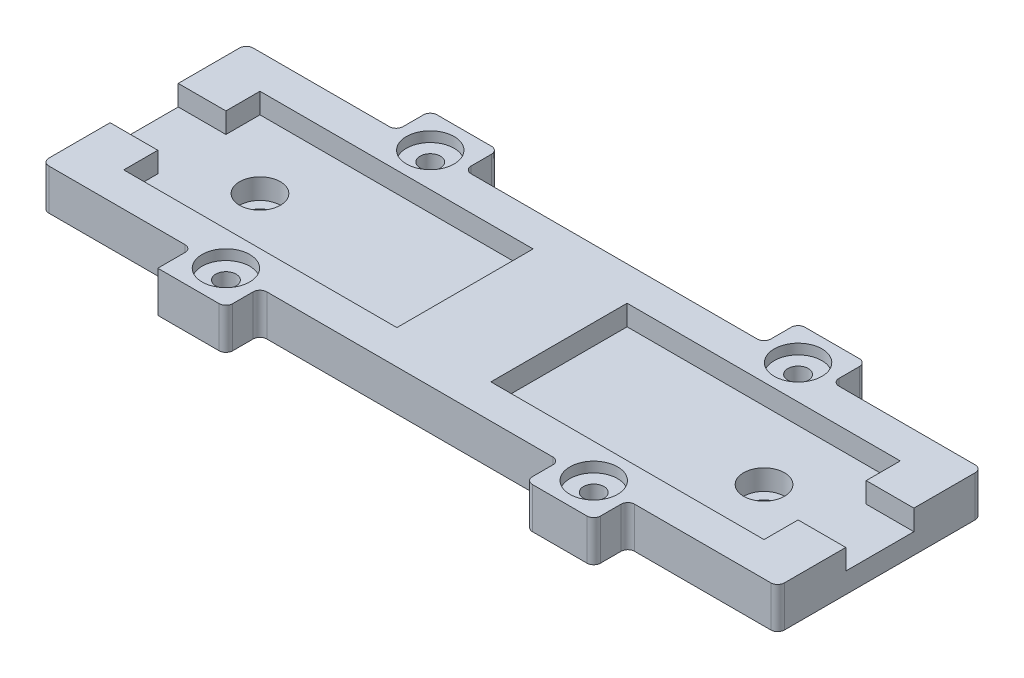
SolidWorks part; units mm, degrees
material "ABS"
ref_plane "前视基准面" through (0, 0, 0) normal (0, 0, 1) x (1, 0, 0)
ref_plane "上视基准面" through (0, 0, 0) normal (0, 1, 0) x (1, 0, 0)
ref_plane "右视基准面" through (0, 0, 0) normal (1, 0, 0) x (0, 0, -1)
sketch "草图1" plane through (0, 0, 0) normal (0, 1, 0) x (1, 0, 0)
  line L0 (-65.1948, 0) -> (81.9903, 0) construction
  line L1 (-54, -15) -> (54, -15)
  line L2 (-54, -15) -> (-54, 15)
  line L3 (-54, 15) -> (54, 15)
  line L4 (54, -15) -> (54, 15)
  line L5 (-54, -15) -> (54, 15) construction
  line L6 (-54, 15) -> (54, -15) construction
  line L7 (0, 35.3859) -> (0, -29.3601) construction
  line L8 (-27, 35.3859) -> (-27, -29.3601) construction
  line L9 (-32, 15) -> (-32, 20)
  line L10 (-32, 20) -> (-22, 20)
  line L11 (-22, 20) -> (-22, 15)
  line L12 (22, 20) -> (22, 15)
  line L13 (32, 20) -> (22, 20)
  line L14 (32, 15) -> (32, 20)
  line L15 (32, -15) -> (32, -20)
  line L16 (32, -20) -> (22, -20)
  line L17 (22, -20) -> (22, -15)
  line L18 (-22, -20) -> (-22, -15)
  line L19 (-32, -20) -> (-22, -20)
  line L20 (-32, -15) -> (-32, -20)
  point P0 (0, 0)
  dimension "D1" = 108
  dimension "D2" = 30
  dimension "D3" = 27
  dimension "D4" = 5
  dimension "D5" = 10
extrude "凸台-拉伸1" add sketch "草图1" along normal blind 6 contours L1 L4 L3 L2 | L11 L10 L9 L3 | L3 L14 L13 L12 | L17 L16 L15 L1 | L1 L20 L19 L18
sketch "草图2" plane through (0, 6, 0) normal (0, 1, 0) x (1, 0, 0)
  line L0 (0, 27.8375) -> (0, -26.4805) construction
  line L7 (-67.1525, 0) -> (66.0954, 0) construction
  circle A0 centre (-27, 15) radius 1.5
  circle A1 centre (27, 15) radius 1.5
  circle A2 centre (27, -15) radius 1.5
  circle A3 centre (-27, -15) radius 1.5
  point P0 (0, 0)
  dimension "D3" = 27
  dimension "D4" = 15
  dimension "D5" = 3
extrude "切除-拉伸1" cut sketch "草图2" against normal blind 6 contours A2 | A3 | A1 | A0
sketch "草图3" plane through (0, 6, 0) normal (0, 1, 0) x (1, 0, 0)
  line L1 (-47, -10) -> (47, -10)
  line L2 (-47, -10) -> (-47, 10)
  line L3 (-47, 10) -> (47, 10)
  line L4 (47, -10) -> (47, 10)
  line L5 (-47, -10) -> (47, 10) construction
  line L6 (-47, 10) -> (47, -10) construction
  point P0 (0, 0)
  dimension "D1" = 94
  dimension "D2" = 20
extrude "切除-拉伸2" cut sketch "草图3" against normal blind 3
sketch "草图4" plane through (0, 0, 0) normal (0, -1, 0) x (1, 0, 0)
  line L0 (-64.4814, 0) -> (67.2508, 0) construction
  line L1 (0, 27.4768) -> (0, -25.5946) construction
  line L3 (-47, -10) -> (-47, 10) construction
  circle A0 centre (-37, 0) radius 6
  circle A1 centre (37, 0) radius 6
  dimension "D1" = 10
  dimension "D2" = 12
extrude "凸台-拉伸2" add sketch "草图4" along normal blind 3.5
sketch "草图5" plane through (0, -3.5, 0) normal (0, -1, 0) x (1, 0, 0)
  line L0 (0, 27.3763) -> (0, -36.667) construction
  circle A0 centre (-37, 0) radius 3
  circle A1 centre (37, 0) radius 3
  dimension "D1" = 6
extrude "切除-拉伸3" cut sketch "草图5" against normal blind 1
sketch "草图6" plane through (0, -2.5, 0) normal (0, -1, 0) x (1, 0, 0)
  line L0 (0, 25.6345) -> (0, -28.5985) construction
  circle A0 centre (-37, 0) radius 1.5
  circle A1 centre (37, 0) radius 1.5
  dimension "D1" = 3
extrude "切除-拉伸4" cut sketch "草图6" against normal through all
sketch "草图7" plane through (0, 3, 0) normal (0, 1, 0) x (1, 0, 0)
  line L0 (0, 24.5482) -> (0, -30.0335) construction
  circle A0 centre (-37, 0) radius 3
  circle A1 centre (37, 0) radius 3
  dimension "D1" = 6
extrude "切除-拉伸5" cut sketch "草图7" against normal blind 3
sketch "草图8" plane through (0, 6, 0) normal (0, 1, 0) x (1, 0, 0)
  line L0 (0, 24.2795) -> (0, -27.8718) construction
  line L1 (-64.8485, 0) -> (72.9003, 0) construction
  circle A0 centre (-27, 15) radius 3.5
  circle A1 centre (27, 15) radius 3.5
  circle A2 centre (27, -15) radius 3.5
  circle A3 centre (-27, -15) radius 3.5
  dimension "D1" = 7
extrude "切除-拉伸6" cut sketch "草图8" against normal blind 1.5
fillet "圆角1" radius 1 19 edges at (-54, 3, 15) (-32, 3, 15) (-22, 3, 15) (-22, 3, 20) (22, 3, 15) (22, 3, 20) (32, 3, 20) (32, 3, 15) (54, 3, 15) (54, 3, -15) (32, 3, -15) (32, 3, -20) (22, 3, -15) (22, 3, -20) (-22, 3, -15) (-22, 3, -20) (-32, 3, -15) (-32, 3, -20) (-54, 3, -15)
sketch "草图9" plane through (-54, 0, 0) normal (-1, 0, 0) x (0, 0, 1)
  line L0 (0, 10.4681) -> (0, -10.097) construction
  line L1 (-5, 6) -> (-5, 3)
  line L2 (14, 6) -> (-14, 6) construction
  line L3 (-5, 3) -> (5, 3)
  line L4 (5, 3) -> (5, 6)
  line L5 (5, 6) -> (-5, 6)
  dimension "D1" = 5
  dimension "D2" = 3
extrude "切除-拉伸7" cut sketch "草图9" against normal through all both and the other way through all
sketch "草图10" plane through (0, 3, 0) normal (0, 1, 0) x (1, 0, 0)
  line L0 (0, 21.44) -> (0, -25.4636) construction
  line L1 (-6.9, -10) -> (-6.9, 10)
  line L2 (-47, -10) -> (47, -10) construction
  line L3 (47, 10) -> (-47, 10) construction
  line L4 (-6.9, 10) -> (6.9, 10)
  line L5 (6.9, 10) -> (6.9, -10)
  line L6 (-47, -10) -> (47, -10) construction
  line L7 (6.9, -10) -> (-6.9, -10)
  line L8 (-47, 10) -> (-47, 5) construction
  dimension "D1" = 40.1
extrude "凸台-拉伸3" add sketch "草图10" along normal up to surface (3 mm away) up to face at (0, 6, -14.5544)
